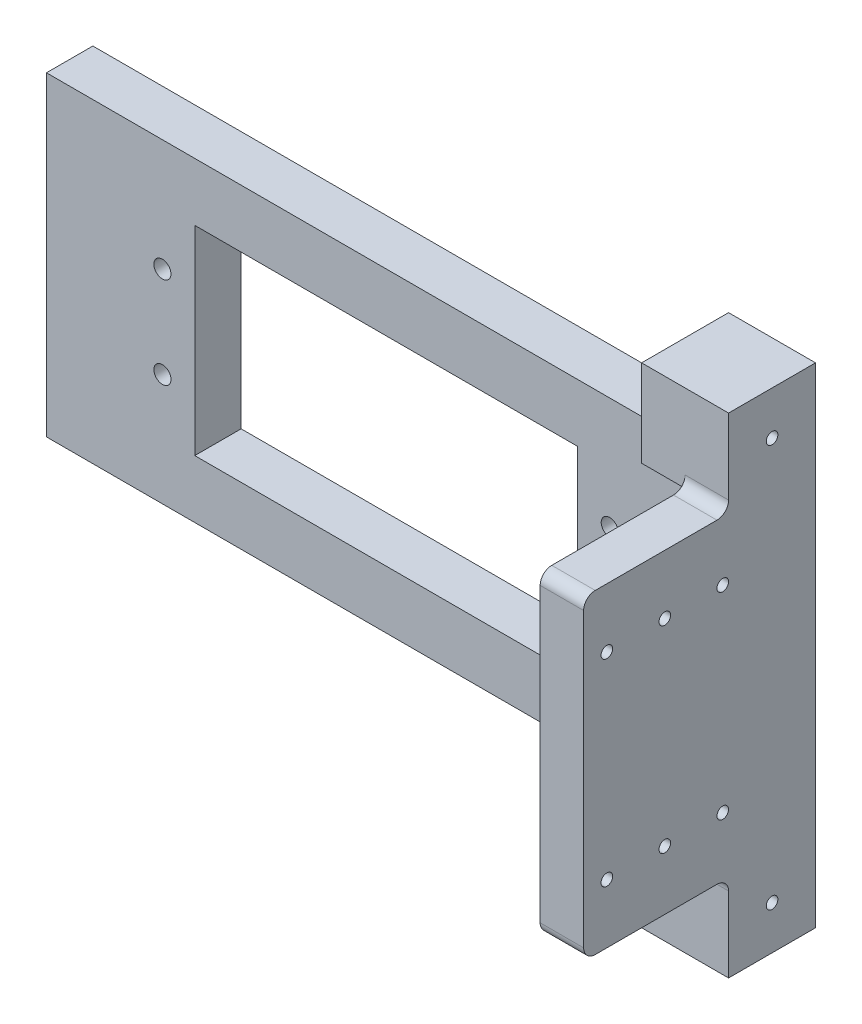
SolidWorks part; units mm, degrees
ref_plane "Front Plane" through (0, 0, 0) normal (0, 0, 1) x (1, 0, 0)
ref_plane "Top Plane" through (0, 0, 0) normal (0, 1, 0) x (1, 0, 0)
ref_plane "Right Plane" through (0, 0, 0) normal (1, 0, 0) x (0, 0, -1)
sketch "Sketch1" plane through (0, 0, 0) normal (0, 0, 1) x (1, 0, 0)
  line L1 (0, 0) -> (54.61, 0)
  line L2 (0, 0) -> (0, 47.244)
  line L3 (0, 47.244) -> (54.61, 47.244)
  line L4 (54.61, 0) -> (54.61, 47.244)
  line L5 (6.35, 12.7) -> (48.26, 12.7)
  line L6 (6.35, 12.7) -> (6.35, 34.544)
  line L7 (6.35, 34.544) -> (48.26, 34.544)
  line L8 (48.26, 12.7) -> (48.26, 34.544)
  dimension "D1" = 41.91
  dimension "D2" = 21.844
  dimension "D3" = 6.35
  dimension "D4" = 6.35
  dimension "D5" = 12.7
  dimension "D6" = 12.7
extrude "Boss-Extrude1" add sketch "Sketch1" along normal blind 5.08
sketch "Sketch2" plane through (0, 0, 5.08) normal (0, 0, 1) x (1, 0, 0)
  line L0 (0, 23.622) -> (54.61, 23.622) construction
  line L1 (2.8054, 28.622) -> (51.8046, 28.622) construction
  line L2 (2.8054, 28.622) -> (2.8054, 18.622) construction
  line L3 (2.8054, 18.622) -> (51.8046, 18.622) construction
  line L4 (51.8046, 28.622) -> (51.8046, 18.622) construction
  line L5 (0, 47.244) -> (0, 0) construction
  line L6 (54.61, 0) -> (54.61, 47.244) construction
  line L7 (2.8054, 23.622) -> (51.8046, 23.622) construction
  line L8 (27.305, 28.622) -> (27.305, 18.622) construction
  line L9 (27.305, 47.244) -> (27.305, 0) construction
  line L10 (54.61, 47.244) -> (0, 47.244) construction
  line L11 (0, 0) -> (54.61, 0) construction
  line L12 (25.1752, 42.164) -> (29.4348, 42.164) construction
  line L13 (29.4348, 42.164) -> (29.4348, 5.08) construction
  line L14 (29.4348, 5.08) -> (25.1752, 5.08) construction
  line L15 (25.1752, 5.08) -> (25.1752, 42.164) construction
  line L16 (48.26, 34.544) -> (6.35, 34.544) construction
  line L17 (6.35, 12.7) -> (48.26, 12.7) construction
  circle A0 centre (2.8054, 28.622) radius 0.936
  circle A1 centre (2.8054, 18.622) radius 0.936
  circle A2 centre (51.8046, 28.622) radius 0.936
  circle A3 centre (51.8046, 18.622) radius 0.936
  circle A4 centre (25.1752, 5.08) radius 0.635 construction
  circle A5 centre (29.4348, 5.08) radius 0.635 construction
  circle A6 centre (29.4348, 42.164) radius 0.635 construction
  circle A7 centre (25.1752, 42.164) radius 0.635 construction
  point P16 (2.8054, 27.686)
  point P17 (2.8054, 19.558)
  dimension "D2" = 8.128
  dimension "D4" = 1.872
  dimension "D5" = 1.27
  dimension "D1" = 10
  dimension "D3" = 48.9991
  dimension "D6" = 4.2596
  dimension "D7" = 2.1298
  dimension "D8" = 7.62
  dimension "D9" = 7.62
  dimension "D10" = 37.084
extrude "Cut-Extrude1" cut sketch "Sketch2" against normal through all
sketch "Sketch10" plane through (0, 0, 5.08) normal (0, 0, 1) x (1, 0, 0)
  line L0 (0, 47.244) -> (0, 80.7756)
  line L1 (0, 80.7756) -> (-31.1018, 80.7756)
  line L2 (0, 47.244) -> (0, 0)
  line L3 (-31.1018, 80.7756) -> (-31.1018, -10.4159)
  line L4 (-31.1018, -10.4159) -> (0, -10.4159)
  line L5 (0, 23.622) -> (54.61, 23.622) construction
  line L6 (54.61, 0) -> (54.61, 47.244) construction
  line L7 (54.61, 23.622) -> (62.23, 23.622) construction
  line L8 (62.23, 23.622) -> (66.4896, 23.622)
  line L9 (-13.8825, 79.8399) -> (-11.43, 79.8399)
  line L10 (-13.8825, 79.8399) -> (-13.8825, 3.6399)
  line L11 (-13.8825, 3.6399) -> (-11.43, 3.6399)
  line L12 (-11.43, 79.8399) -> (-11.43, 3.6399)
  line L13 (0, -10.4159) -> (0, 47.244)
  line L14 (69.0296, 23.622) -> (66.4896, 23.622) construction
  line L15 (0, 47.244) -> (0, 0) construction
  line L16 (64.3598, 25.7518) -> (64.3598, 21.4922) construction
  line L17 (54.61, 33.3718) -> (69.0296, 33.3718)
  line L18 (54.61, 33.3718) -> (54.61, 13.8722)
  line L19 (54.61, 13.8722) -> (69.0296, 13.8722)
  line L20 (69.0296, 33.3718) -> (69.0296, 13.8722)
  line L21 (0, 0) -> (54.61, 0) construction
  line L23 (54.61, 13.1354) -> (54.5843, 13.1354)
  circle A0 centre (-6.7996, 44.704) radius 0.635
  circle A1 centre (-2.54, 44.704) radius 0.635
  circle A2 centre (62.23, 23.622) radius 0.635 construction
  circle A3 centre (66.4896, 23.622) radius 0.635 construction
  circle A4 centre (64.3598, 25.7518) radius 0.635
  circle A5 centre (64.3598, 21.4922) radius 0.635
  point P27 (64.3598, 23.622)
  dimension "D1" = 1.27
  dimension "D10" = 13.8825
  dimension "D11" = 31.1018
  dimension "D2" = 4.2596
  dimension "D3" = 7.62
  dimension "D4" = 2.54
  dimension "D5" = 7.62
  dimension "D6" = 76.2
  dimension "D7" = 2.54
  dimension "D8" = 11.43
  dimension "D9" = 54.5843
  dimension "D12" = 3.6399
  dimension "D13" = 13.1354
  dimension "D14" = 44.704
  dimension "D15" = 80.7756
  dimension "D16" = 10.4159
  dimension "D17" = 4.2596
extrude "Boss-Extrude4" add sketch "Sketch10" against normal up to surface (5.08 mm away)
sketch "Sketch11" plane through (0, 0, 5.08) normal (0, 0, 1) x (1, 0, 0)
  line L0 (0, 47.244) -> (-5.842, 47.244)
  line L1 (-5.842, 47.244) -> (-5.842, 64.262)
  line L2 (-5.842, 64.262) -> (-15.748, 64.262)
  line L3 (-15.748, 64.262) -> (-15.748, -17.018)
  line L4 (-15.748, -17.018) -> (-4.572, -17.018)
  line L5 (-4.572, -17.018) -> (-4.572, 0)
  line L6 (-4.572, 0) -> (0, 0)
  line L7 (0, 0) -> (0, 47.244)
  line L11 (-9.144, 61.722) -> (-5.842, 61.722) construction
  line L12 (-12.446, 61.722) -> (-9.144, 61.722)
  line L13 (-12.446, 61.722) -> (-12.446, -14.478)
  line L14 (-12.446, -14.478) -> (-9.144, -14.478)
  line L15 (-9.144, 61.722) -> (-9.144, -14.478)
  line L16 (-12.446, 61.722) -> (-15.748, 61.722) construction
  line L17 (-12.446, 61.722) -> (-12.446, 64.262) construction
  line L18 (-12.446, -14.478) -> (-12.446, -17.018) construction
  line L19 (0, 47.244) -> (0, 0) construction
  line L20 (0, 0) -> (54.61, 0) construction
  circle A0 centre (64.3598, 25.7518) radius 0.635 construction
  circle A1 centre (64.3598, 21.4922) radius 0.635 construction
  circle A2 centre (64.3598, 25.7518) radius 0.635 construction
  circle A3 centre (64.3598, 21.4922) radius 0.635 construction
  circle A4 centre (-4.572, 21.4922) radius 0.635
  circle A5 centre (-4.572, 25.7518) radius 0.635
  dimension "D10" = 1.27
  dimension "D1" = 76.2
  dimension "D2" = 4.572
  dimension "D3" = 4.572
  dimension "D4" = 3.302
  dimension "D5" = 3.302
  dimension "D6" = 81.28
  dimension "D7" = 15.748
  dimension "D8" = 4.572
  dimension "D9" = 0
  dimension "D11" = 4.2596
  dimension "D12" = 4.572
  dimension "D13" = 21.4922
extrude "Boss-Extrude5" add sketch "Sketch11" against normal up to surface (5.08 mm away) up to face at (52.7406, 18.622, 0)
sketch "Sketch12" plane through (0, 0, 5.08) normal (0, 0, 1) x (1, 0, 0)
  line L0 (54.61, 33.3718) -> (54.61, 47.244) construction
  line L1 (-5.842, 47.244) -> (54.61, 47.244)
  line L2 (-5.842, 47.244) -> (-5.842, 40.894)
  line L3 (-5.842, 40.894) -> (54.61, 40.894)
  line L4 (54.61, 47.244) -> (54.61, 40.894)
  line L5 (54.61, 0) -> (54.61, 13.8722) construction
  line L6 (-4.572, 0) -> (54.61, 0)
  line L7 (-4.572, 0) -> (-4.572, 6.35)
  line L8 (-4.572, 6.35) -> (54.61, 6.35)
  line L9 (54.61, 0) -> (54.61, 6.35)
  line L10 (6.35, 12.7) -> (48.26, 12.7) construction
  line L11 (48.26, 34.544) -> (6.35, 34.544) construction
  line L12 (48.26, 12.7) -> (48.26, 34.544) construction
  line L13 (48.26, 12.7) -> (48.26, 34.544) construction
  dimension "D1" = 6.35
  dimension "D2" = 6.35
  dimension "D3" = 6.35
extrude "Cut-Extrude2" cut sketch "Sketch12" against normal through all
sketch "Sketch13" plane through (0, 0, 0) normal (0, 0, -1) x (-1, 0, 0)
  line L0 (15.748, 64.262) -> (15.748, -17.018) construction
  line L1 (7.1554, 62.8847) -> (14.175, 62.8847)
  line L2 (7.1554, 62.8847) -> (7.1554, -16.1087)
  line L3 (7.1554, -16.1087) -> (14.175, -16.1087)
  line L4 (14.175, 62.8847) -> (14.175, -16.1087)
  line L5 (9.144, 61.722) -> (12.446, 61.722) construction
  line L6 (12.446, -14.478) -> (9.144, -14.478) construction
  dimension "D1" = 7.0196
  dimension "D2" = 1.573
  dimension "D3" = 1.1627
  dimension "D4" = 1.6307
extrude "Boss-Extrude6" add sketch "Sketch13" against normal offset from surface (4.826 mm away) 0.254 up to face at (52.7406, 18.622, 5.08)
fillet "Fillet1" radius 2.54 12 edges at (69.0296, 13.8722, 2.54) (54.61, 6.35, 2.54) (-4.572, 6.35, 2.54) (-4.572, -17.018, 2.54) (-15.748, -17.018, 2.54) (-15.748, 64.262, 2.54) (-5.842, 64.262, 2.54) (-5.842, 40.894, 2.54) (54.61, 40.894, 2.54) (69.0296, 33.3718, 2.54)
sketch "Sketch14" plane through (0, 0, 5.08) normal (0, 0, 1) x (1, 0, 0)
  line L0 (2.8054, 28.622) -> (2.8054, 40.894) construction
  line L1 (-3.302, 40.894) -> (52.07, 40.894) construction
  line L2 (2.8054, 40.894) -> (-0.8159, 40.894)
  line L3 (-0.8159, 40.894) -> (-0.8159, 6.35)
  line L5 (52.07, 6.35) -> (-2.032, 6.35) construction
  line L6 (-0.8159, 6.35) -> (2.8054, 6.35)
  line L7 (2.8054, 6.35) -> (2.8054, -19.9418)
  line L8 (2.8054, -19.9418) -> (-23.5153, -19.9418)
  line L9 (-23.5153, -19.9418) -> (-23.5153, 65.8265)
  line L10 (-23.5153, 65.8265) -> (2.8054, 65.8265)
  line L11 (2.8054, 65.8265) -> (2.8054, 40.894)
  line L12 (51.8046, 28.622) -> (51.8046, 40.8969) construction
  line L13 (51.8046, 40.8969) -> (51.8046, 65.8265)
  line L14 (51.8046, 65.8265) -> (74.4862, 65.8265)
  line L15 (74.4862, 65.8265) -> (74.4862, -19.9418)
  line L16 (74.4862, -19.9418) -> (51.8046, -19.9418)
  line L17 (51.8046, -19.9418) -> (52.07, 6.35)
  line L18 (52.07, 6.35) -> (54.61, 8.89)
  line L19 (54.61, 8.89) -> (54.61, 38.354)
  line L20 (54.61, 38.354) -> (51.8046, 40.8969)
  line L21 (-15.748, 61.722) -> (-15.748, -14.478) construction
  line L22 (-8.382, 64.262) -> (-13.208, 64.262) construction
  dimension "D1" = 14.9321
  dimension "D2" = 90.2342
  dimension "D3" = 7.7673
  dimension "D4" = 1.5645
  dimension "D5" = 23.3651
  dimension "D6" = 84.2038
extrude "Cut-Extrude3" cut sketch "Sketch14" against normal through all
sketch "Sketch15" plane through (0, 0, 5.08) normal (0, 0, 1) x (1, 0, 0)
  line L0 (-0.8159, 40.894) -> (-9.8946, 40.894)
  line L1 (-9.8946, 40.894) -> (-9.8946, 6.35)
  line L2 (-9.8946, 6.35) -> (-0.8159, 6.35)
  line L3 (-0.8159, 6.35) -> (-0.8159, 40.894) construction
  line L4 (-0.8159, 6.35) -> (-0.8159, 40.894)
  line L5 (51.8077, 40.894) -> (54.61, 38.354)
  line L6 (54.61, 38.354) -> (54.61, 8.89)
  line L7 (54.61, 8.89) -> (54.61, 38.354) construction
  line L8 (54.61, 8.89) -> (52.07, 6.35)
  line L9 (52.07, 6.35) -> (64.5046, 6.35)
  line L10 (64.5046, 6.35) -> (64.5046, 40.894)
  line L11 (64.5046, 40.894) -> (51.8077, 40.894)
  circle A0 centre (2.8054, 28.622) radius 0.936 construction
  circle A1 centre (2.8054, 28.622) radius 0.936 construction
  circle A2 centre (51.8046, 28.622) radius 0.936 construction
  circle A3 centre (51.8046, 28.622) radius 0.936 construction
  dimension "D1" = 12.7
  dimension "D2" = 3.6214
  dimension "D3" = 12.7
extrude "Boss-Extrude7" add sketch "Sketch15" against normal up to surface (5.08 mm away) up to face at (35.2443, 21.1667, 0)
sketch "Sketch19" plane through (64.5046, 0, 0) normal (1, 0, 0) x (0, 0, -1)
  line L0 (0, 40.894) -> (-5.08, 40.894) construction
  line L1 (0, 6.35) -> (-25.4, 6.35)
  line L2 (0, 6.35) -> (0, 40.894)
  line L3 (0, 40.894) -> (-25.4, 40.894)
  line L4 (-25.4, 6.35) -> (-25.4, 40.894)
  dimension "D1" = 25.4
extrude "Boss-Extrude9" add sketch "Sketch19" along normal blind 4.7625
sketch "Sketch20" plane through (69.2671, 0, 0) normal (1, 0, 0) x (0, 0, -1)
  line L1 (0, 40.894) -> (-9.525, 40.894)
  line L2 (0, 40.894) -> (0, 50.419)
  line L3 (0, 50.419) -> (-9.525, 50.419)
  line L4 (-9.525, 40.894) -> (-9.525, 50.419)
  line L5 (0, 6.35) -> (-9.525, 6.35)
  line L6 (0, 6.35) -> (0, -3.175)
  line L7 (0, -3.175) -> (-9.525, -3.175)
  line L8 (-9.525, 6.35) -> (-9.525, -3.175)
  dimension "D1" = 9.525
  dimension "D2" = 9.525
  dimension "D3" = 9.525
  dimension "D4" = 9.525
extrude "Boss-Extrude10" add sketch "Sketch20" against normal blind 9.525
sketch "Sketch21" plane through (69.2671, 0, 0) normal (1, 0, 0) x (0, 0, -1)
  line L0 (-9.525, 40.894) -> (0, 50.419) construction
  line L4 (-9.525, 6.35) -> (0, -3.175) construction
  circle A0 centre (-4.7625, 45.6565) radius 0.635
  circle A1 centre (-4.7625, 1.5875) radius 0.635
  point P5 (-4.7625, 45.6565)
  point P7 (-4.7625, 1.5875)
  dimension "D1" = 1.27
  dimension "D2" = 1.27
extrude "Cut-Extrude4" cut sketch "Sketch21" against normal through all
sketch "Sketch22" plane through (69.2671, 0, 0) normal (1, 0, 0) x (0, 0, -1)
  line L0 (0, 23.622) -> (-25.4, 23.622) construction
  line L1 (-3.81, 34.417) -> (-22.86, 34.417) construction
  line L2 (-3.81, 34.417) -> (-3.81, 12.827) construction
  line L3 (-3.81, 12.827) -> (-22.86, 12.827) construction
  line L4 (-22.86, 34.417) -> (-22.86, 12.827) construction
  line L5 (0, -3.175) -> (0, 50.419) construction
  line L6 (-25.4, 40.894) -> (-25.4, 6.35) construction
  circle A0 centre (-22.86, 34.417) radius 0.635
  circle A1 centre (-22.86, 12.827) radius 0.635
  circle A2 centre (-3.81, 12.827) radius 0.635 construction
  circle A3 centre (-3.81, 34.417) radius 0.635 construction
  circle A4 centre (-16.51, 34.417) radius 0.635
  circle A5 centre (-10.16, 34.417) radius 0.635
  circle A6 centre (-10.16, 12.827) radius 0.635
  circle A7 centre (-16.51, 12.827) radius 0.635
  point P10 (-22.86, 23.622)
  dimension "D4" = 1.27
  dimension "D5" = 1.27
  dimension "D1" = 21.59
  dimension "D2" = 19.05
  dimension "D3" = 2.54
  dimension "D6" = 6.35
  dimension "D7" = 6.35
  dimension "D8" = 6.35
  dimension "D9" = 6.35
extrude "Cut-Extrude5" cut sketch "Sketch22" against normal through all
ref_plane "Plane1" through (0, 23.622, 0) normal (0, -1, 0) x (-1, 0, 0)
sketch "Sketch24" plane through (0, 23.622, 0) normal (0, -1, 0) x (-1, 0, 0)
  line L0 (-64.5046, -12.7) -> (-56.8846, -5.08)
  line L1 (-64.5046, -25.4) -> (-64.5046, -9.525) construction
  line L2 (-59.7421, -5.08) -> (9.8946, -5.08) construction
  line L3 (-69.2671, -25.4) -> (-64.5046, -25.4) construction
  dimension "D1" = 12.7
  dimension "D2" = 45
rib "Rib1" sketch "Sketch24" sketch "Sketch24" thickness 2.54 extrusion direction parallel to sketch draft on no parameters "D1"=2.54
fillet "Fillet2" radius 1.27 18 edges at (66.8858, 40.894, 25.4) (66.8858, 6.35, 25.4) (64.5046, 23.622, 12.7) (56.8846, 23.622, 5.08) (60.6946, 22.352, 5.08) (60.6946, 24.892, 5.08)
equation "\"D7@Sketch2\"=\"D6@Sketch2\"/2"
equation "\"D8@Sketch11\" = \"D2@Sketch11\""
equation "\"D3@Sketch11\"= \"D2@Sketch11\""
